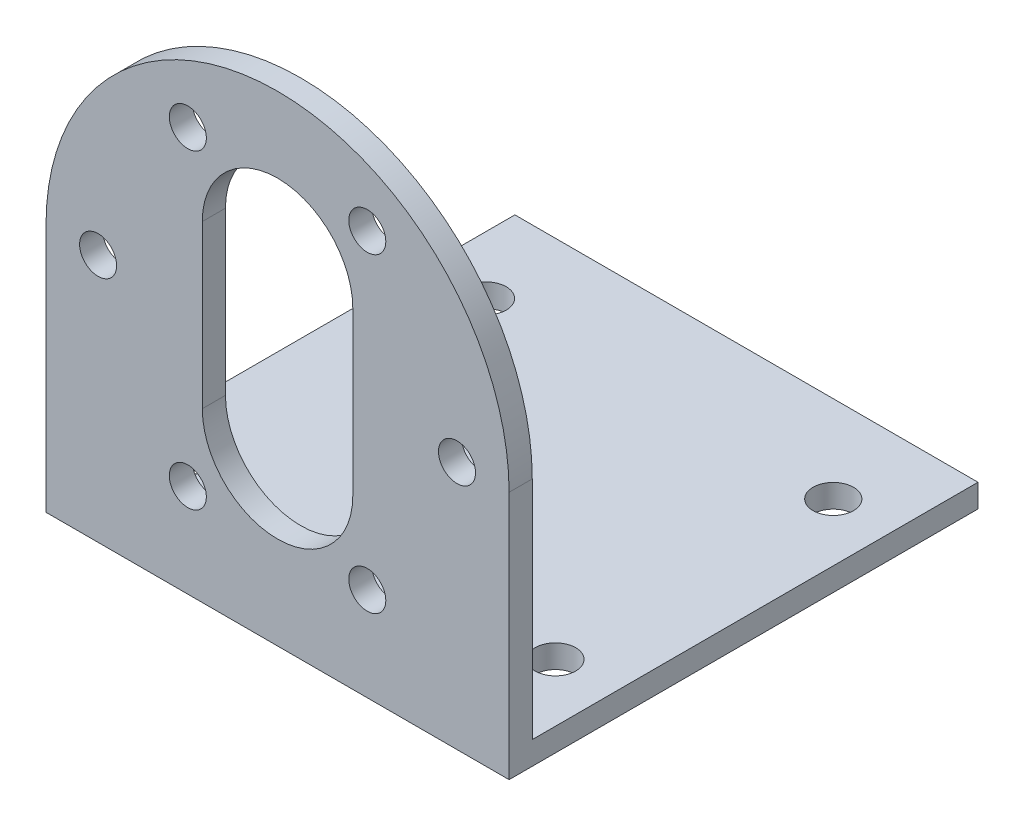
SolidWorks part; units mm, degrees
ref_plane "前视基准面" through (0, 0, 0) normal (0, 0, 1) x (1, 0, 0)
ref_plane "上视基准面" through (0, 0, 0) normal (0, 1, 0) x (1, 0, 0)
ref_plane "右视基准面" through (0, 0, 0) normal (1, 0, 0) x (0, 0, -1)
other "Configuration Table"
ref_plane "基准面1" through (0, 0, 20.25) normal (0, 0, 1) x (1, 0, 0)
sketch "草图1" plane through (0, 0, 20.25) normal (0, 0, 1) x (1, 0, 0)
  line L0 (20, -2) -> (20, 19.5)
  line L1 (-20, 19.5) -> (-20, -2)
  line L2 (-20, -2) -> (20, -2)
  arc A0 (20, 19.5) -> (-20, 19.5) centre (0, 19.5) ccw
extrude "凸台-拉伸1" add sketch "草图1" against normal blind 40.5
sketch "草图2" plane through (20, 0, 0) normal (1, 0, 0) x (0, 0, -1)
  line L0 (20.25, 19.5) -> (-18.25, 19.5)
  line L1 (-18.25, 19.5) -> (-18.25, 0)
  line L2 (-18.25, 0) -> (20.25, 0)
  line L3 (20.25, 0) -> (20.25, 19.5)
extrude "切除-拉伸1" cut sketch "草图2" against normal through all
sketch "草图3" plane through (0, 0, 20.25) normal (0, 0, 1) x (1, 0, 0)
  line L0 (-6.5, 26.5) -> (-6.5, 12.5)
  line L1 (6.5, 12.5) -> (6.5, 26.5)
  arc A0 (6.5, 26.5) -> (-6.5, 26.5) centre (0, 26.5) ccw
  arc A1 (-6.5, 12.5) -> (6.5, 12.5) centre (0, 12.5) ccw
extrude "切除-拉伸2" cut sketch "草图3" against normal blind 2
hole_wizard "Ø3.5 (3.5) 直径孔1" positions "草图5" profile "草图4" hole size "Ø3.5" standard "ANSI Metric"
sketch "草图5" plane through (0, -2, 0) normal (0, -1, 0) x (-1, 0, 0)
  point P0 (15, -11.25)
  point P1 (15, 12.75)
  point P2 (-15, 12.75)
  point P3 (-15, -11.25)
sketch "草图4" plane through (-15, -2, 11.25) normal (1, 0, 0) x (0, 0, -1)
  line L0 (0, 0) -> (0, 2)
  line L1 (0, 2) -> (1.75, 2)
  line L2 (1.75, 2) -> (1.75, 0)
  line L5 (1.75, 0) -> (0, 0)
  line L11 (0, -6.35) -> (0, 107.95) construction
  dimension "通孔孔直径" = 3.5
  dimension "通孔孔深度" = 2
hole_wizard "Ø3.2 (3.2) 直径孔1" positions "草图7" profile "草图6" hole size "Ø3.2" standard "ANSI Metric"
sketch "草图7" plane through (0, 0, 20.25) normal (0, 0, 1) x (1, 0, 0)
  point P0 (-7.75, 32.9234)
  point P1 (-7.75, 6.0766)
  point P2 (15.5, 19.5)
  point P3 (7.75, 6.0766)
  point P4 (-15.5, 19.5)
  point P5 (7.75, 32.9234)
sketch "草图6" plane through (-7.75, 32.9234, 20.25) normal (1, 0, 0) x (0, -1, 0)
  line L0 (0, 0) -> (0, 40.5)
  line L1 (0, 40.5) -> (1.6, 40.5)
  line L2 (1.6, 40.5) -> (1.6, 0)
  line L5 (1.6, 0) -> (0, 0)
  line L11 (0, -6.35) -> (0, 107.95) construction
  dimension "通孔孔直径" = 3.2
  dimension "通孔孔深度" = 40.5
sketch "草图12" plane through (0, 0, -20.25) normal (0, 0, -1) x (-1, 0, 0)
  line L0 (20, 19.5) -> (17.1, 19.5) construction
  line L1 (-17.1, 19.5) -> (-20, 19.5) construction
  line L2 (-20, 19.5) -> (-17.1, 19.5)
  line L3 (-13.9, 19.5) -> (13.9, 19.5)
  line L4 (17.1, 19.5) -> (20, 19.5)
  arc A0 (-13.9, 19.5) -> (-17.1, 19.5) centre (-15.5, 19.5) ccw
  arc A1 (-13.9, 19.5) -> (-17.1, 19.5) centre (-15.5, 19.5) ccw construction
  arc A2 (17.1, 19.5) -> (13.9, 19.5) centre (15.5, 19.5) ccw
  arc A3 (17.1, 19.5) -> (13.9, 19.5) centre (15.5, 19.5) ccw construction
  arc A4 (20, 19.5) -> (-20, 19.5) centre (0, 19.5) ccw
  circle A5 centre (-7.75, 32.9234) radius 1.6
  circle A6 centre (7.75, 32.9234) radius 1.6
  arc A7 (20, 19.5) -> (-20, 19.5) centre (0, 19.5) ccw construction
extrude "切除-拉伸3" cut sketch "草图12" against normal blind 38.5
sketch "草图13" plane through (0, 0, -20.25) normal (0, 0, -1) x (-1, 0, 0)
  line L1 (-20, 0) -> (20, 0)
  line L2 (-20, 0) -> (-20, -2)
  line L3 (-20, -2) -> (20, -2)
  line L4 (20, 0) -> (20, -2)
sketch "草图14" plane through (20, 0, 0) normal (1, 0, 0) x (0, 0, -1)
  line L0 (-18.25, 0) -> (-18.25, -2)
  line L1 (20.25, -2) -> (-20.25, -2) construction
  line L2 (-18.25, -2) -> (-20.25, -2)
  line L4 (-13, -2) -> (-9.5, -2) construction
sketch "草图15" plane through (0, -2, 0) normal (0, -1, 0) x (1, 0, 0)
  line L0 (19.5465, 18.25) -> (-20, 18.25)
  line L1 (-20, -20.25) -> (-20, 20.25) construction
  line L2 (-20, 18.25) -> (-20, 20.25)
  line L3 (-20, 20.25) -> (20, 20.25)
sketch "草图16" plane through (0, 0, 20.25) normal (0, 0, 1) x (1, 0, 0)
  line L0 (0, 26.5) -> (0, 12.5) construction
  line L1 (6.517, 26.5) -> (6.517, 12.5)
  line L2 (-6.517, 26.5) -> (-6.517, 12.5)
  line L3 (15.5, 19.5) -> (7.75, 32.9234)
  line L4 (7.75, 32.9234) -> (-7.75, 32.9234)
  line L5 (-7.75, 32.9234) -> (-15.5, 19.5)
  line L6 (-15.5, 19.5) -> (-7.75, 6.0766)
  line L7 (-7.75, 6.0766) -> (7.75, 6.0766)
  line L8 (7.75, 6.0766) -> (15.5, 19.5)
  line L10 (19.5465, -2) -> (-20, -2) construction
  circle A0 centre (15.5, 19.5) radius 1.6
  circle A3 centre (7.75, 32.9234) radius 1.6
  circle A4 centre (7.75, 6.0766) radius 1.6
  circle A5 centre (-7.75, 32.9234) radius 1.6
  circle A6 centre (-7.75, 6.0766) radius 1.6
  circle A7 centre (-15.5, 19.5) radius 1.6
  arc A8 (6.517, 26.5) -> (-6.517, 26.5) centre (0, 26.5) ccw
  arc A9 (-6.517, 12.5) -> (6.517, 12.5) centre (0, 12.5) ccw
  circle A10 centre (0, 19.5) radius 13.4234
  point P23 (0, 19.5)
sketch "草图17" plane through (0, -2, 0) normal (0, -1, 0) x (1, 0, 0)
  line L2 (-20, 18.25) -> (20, 18.25)
  line L3 (-20, 18.25) -> (-20, 20.25)
  line L4 (-20, 20.25) -> (20, 20.25)
  line L5 (20, 18.25) -> (20, 20.25)
